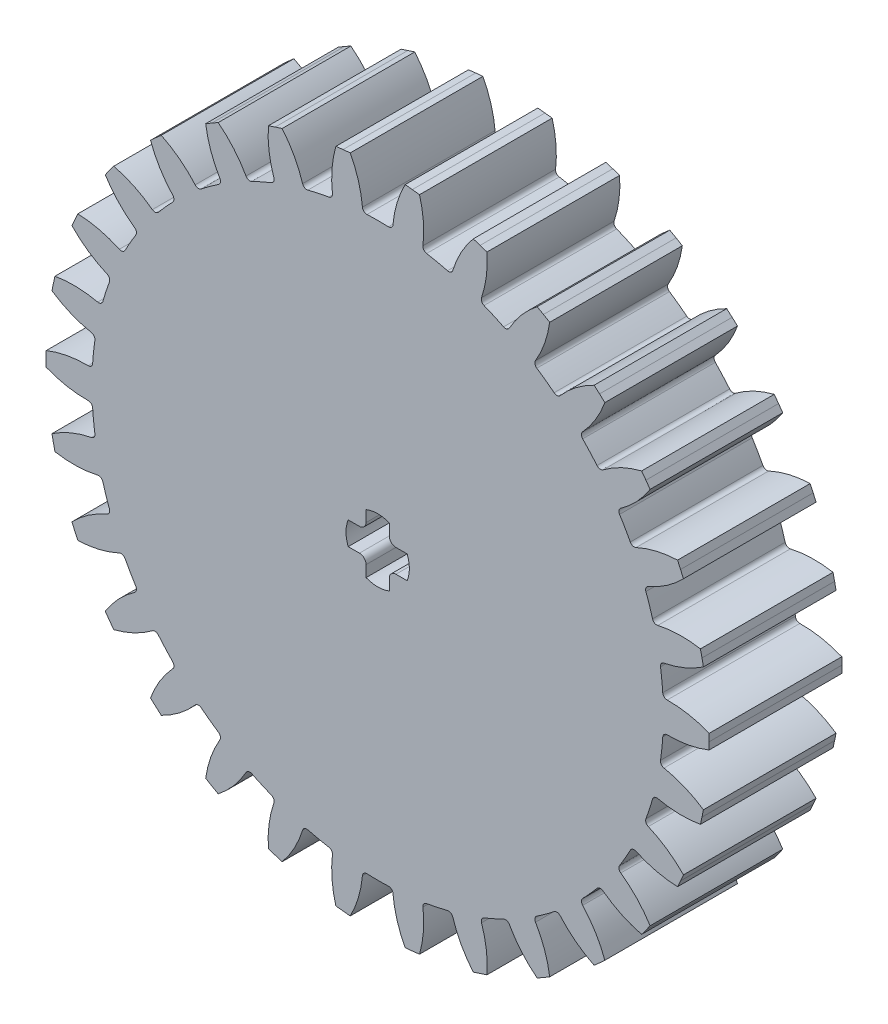
SolidWorks part; units mm, degrees
ref_plane "Front Plane" through (0, 0, 0) normal (0, 0, 1) x (1, 0, 0)
ref_plane "Top Plane" through (0, 0, 0) normal (0, 1, 0) x (1, 0, 0)
ref_plane "Right Plane" through (0, 0, 0) normal (1, 0, 0) x (0, 0, -1)
sketch "Sketch1" plane through (0, 0, 0) normal (0, 0, 1) x (1, 0, 0)
  line L0 (0, 0) -> (74.4139, 0) construction
  line L1 (0, 0) -> (21.4245, 2.2518) construction
  line L2 (0, 0) -> (74.4139, 3.8999) construction
  line L3 (0, 0) -> (74.4139, 1.6237) construction
  line L4 (24.9941, 0.5454) -> (25, 0)
  line L5 (0, 0) -> (21.4245, -2.2518) construction
  line L6 (0, 0) -> (21.4245, 2.2518)
  line L7 (0, 0) -> (21.4245, -2.2518) construction
  line L8 (0, 0) -> (21.4245, -2.2518)
  line L9 (24.9941, -0.5454) -> (25, 0)
  circle A0 centre (0, 0) radius 25 construction
  circle A1 centre (0, 0) radius 23.4375 construction
  circle A2 centre (0, 0) radius 21.5425 construction
  arc A3 (21.513, 1.1274) -> (24.9941, 0.5454) centre (21.9399, -7.0194) cw
  arc A4 (21.513, 1.1274) -> (21.4245, 2.2518) centre (0, 0) ccw
  arc A5 (21.513, -1.1274) -> (21.4245, -2.2518) centre (0, 0) cw
  arc A6 (21.513, -1.1274) -> (24.9941, -0.5454) centre (21.9399, 7.0194) ccw
  dimension "D1" = 50
  dimension "D2" = 1.5625
  dimension "D7" = 1.895
  dimension "D4" = 6
  dimension "D5" = 3
  dimension "D6" = 1.25
extrude "Boss-Extrude1" add sketch "Sketch1" along normal blind 10
fillet "Fillet1" radius 0.3325 2 edges at (21.513, 1.1274, 5) (21.513, -1.1274, 5)
pattern_circular "CirPattern1" count 30 over 360 about axis through (0, 0, 0) along (0, 0, 1) of "Boss-Extrude1", "Fillet1"
sketch "Sketch2" plane through (0, 0, 0) normal (0, 0, -1) x (-1, 0, 0)
  line L0 (0.875, 2.2241) -> (0.875, 1.375)
  line L1 (1.375, 0.875) -> (2.2241, 0.875)
  line L2 (2.39, 0) -> (-2.39, 0) construction
  line L3 (0, 2.39) -> (0, -2.39) construction
  line L4 (1.375, -0.875) -> (2.2241, -0.875)
  line L5 (0.875, -2.2241) -> (0.875, -1.375)
  line L6 (-0.875, -2.2241) -> (-0.875, -1.375)
  line L7 (-1.375, -0.875) -> (-2.2241, -0.875)
  line L8 (-1.375, 0.875) -> (-2.2241, 0.875)
  line L9 (-0.875, 2.2241) -> (-0.875, 1.375)
  arc A0 (-2.2241, -0.875) -> (-2.2241, 0.875) centre (0, 0) cw
  circle A1 centre (0, 0) radius 2.39 construction
  circle A2 centre (0, 0) radius 1.2374 construction
  arc A3 (-0.875, 2.2241) -> (0.875, 2.2241) centre (0, 0) cw
  arc A4 (-1.375, -0.875) -> (-0.875, -1.375) centre (-1.375, -1.375) cw
  arc A5 (0.875, -2.2241) -> (-0.875, -2.2241) centre (0, 0) cw
  arc A6 (2.2241, 0.875) -> (2.2241, -0.875) centre (0, 0) cw
  arc A7 (1.375, -0.875) -> (0.875, -1.375) centre (1.375, -1.375) ccw
  arc A8 (1.375, 0.875) -> (0.875, 1.375) centre (1.375, 1.375) cw
  arc A9 (-1.375, 0.875) -> (-0.875, 1.375) centre (-1.375, 1.375) ccw
  point P6 (0, 0)
  dimension "D1" = 4.78
  dimension "D2" = 0.5
  dimension "D3" = 1.75
  dimension "D4" = 1.75
extrude "Cut-Extrude1" cut sketch "Sketch2" against normal up to next
